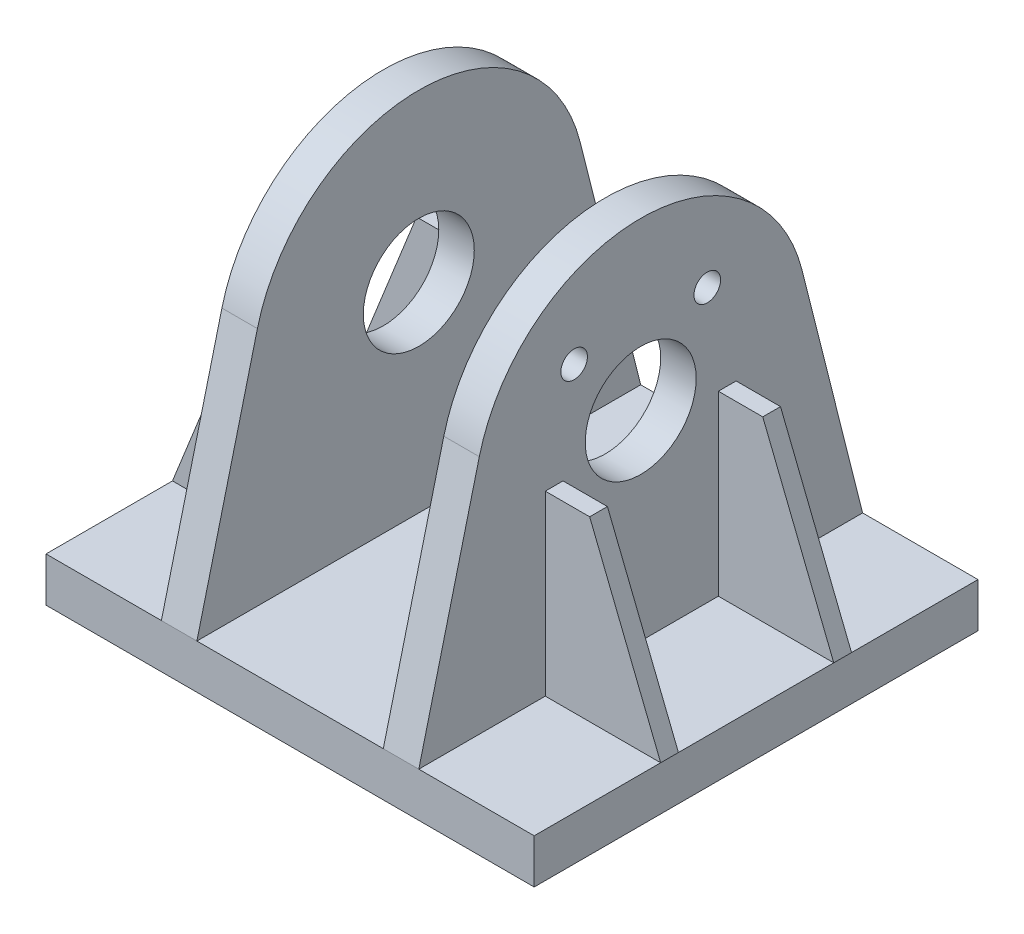
SolidWorks part; units mm, degrees
ref_plane "前视基准面" through (0, 0, 0) normal (0, 0, 1) x (1, 0, 0)
ref_plane "上视基准面" through (0, 0, 0) normal (0, 1, 0) x (1, 0, 0)
ref_plane "右视基准面" through (0, 0, 0) normal (1, 0, 0) x (0, 0, -1)
sketch "草图1" plane through (0, 0, 0) normal (0, 1, 0) x (1, 0, 0)
  line L1 (-110, 100) -> (110, 100)
  line L2 (-110, 100) -> (-110, -100)
  line L3 (-110, -100) -> (110, -100)
  line L4 (110, 100) -> (110, -100)
  dimension "D1" = 100
  dimension "D2" = 100
  dimension "D3" = 110
  dimension "D4" = 110
extrude "凸台-拉伸1" add sketch "草图1" along normal blind 20
sketch "草图2" plane through (0, 20, 0) normal (0, 1, 0) x (1, 0, 0)
  line L1 (110, 100) -> (-110, 100) construction
  line L2 (-58, 100) -> (-42, 100)
  line L3 (-58, 100) -> (-58, -100)
  line L4 (-58, -100) -> (-42, -100)
  line L5 (-42, 100) -> (-42, -100)
  line L6 (-110, -100) -> (110, -100) construction
  line L8 (42, 100) -> (58, 100)
  line L9 (42, 100) -> (42, -100)
  line L10 (42, -100) -> (58, -100)
  line L11 (58, 100) -> (58, -100)
  dimension "D1" = 16
  dimension "D2" = 16
  dimension "D3" = 42
  dimension "D4" = 42
extrude "凸台-拉伸2" add sketch "草图2" along normal blind 200
sketch "草图3" plane through (58, 0, 0) normal (1, 0, 0) x (0, 0, -1)
  line L0 (0, -1000) -> (0, 49000) construction
  line L1 (-100, 20) -> (100, 20) construction
  line L2 (-72.7303, 128.3114) -> (-100, 20)
  line L3 (-100, 20) -> (-100, 220)
  line L4 (-100, 220) -> (100, 220)
  line L5 (100, 220) -> (100, 20)
  line L6 (100, 20) -> (72.7303, 128.3114)
  circle A0 centre (0, 110) radius 25
  arc A1 (72.7303, 128.3114) -> (-72.7303, 128.3114) centre (0, 110) ccw
  dimension "D1" = 50
  dimension "D3" = 75
  dimension "D2" = 90
extrude "切除-拉伸1" cut sketch "草图3" against normal through all
sketch "草图4" plane through (58, 0, 0) normal (1, 0, 0) x (0, 0, -1)
  line L0 (-100, 20) -> (100, 20) construction
  line L1 (-43, 100) -> (-35, 100)
  line L2 (-43, 100) -> (-43, 20)
  line L3 (-43, 20) -> (-35, 20)
  line L4 (-35, 100) -> (-35, 20)
  line L6 (35, 100) -> (43, 100)
  line L7 (35, 100) -> (35, 20)
  line L8 (35, 20) -> (43, 20)
  line L9 (43, 100) -> (43, 20)
  dimension "D1" = 8
  dimension "D2" = 8
  dimension "D3" = 80
  dimension "D4" = 35
  dimension "D5" = 35
extrude "凸台-拉伸3" add sketch "草图4" along normal blind 52
sketch "草图5" plane through (0, 0, 43) normal (0, 0, 1) x (1, 0, 0)
  line L0 (110, 100) -> (78, 100)
  line L1 (110, 100) -> (58, 100) construction
  line L2 (78, 100) -> (110, 20)
  line L3 (110, 20) -> (110, 100)
  dimension "D1" = 32
extrude "切除-拉伸2" cut sketch "草图5" against normal through all
mirror "镜向1" about plane through (0, 0, 0) normal (1, 0, 0) of "切除-拉伸2", "凸台-拉伸3"
sketch "草图6" plane through (58, 0, 0) normal (1, 0, 0) x (0, 0, -1)
  line L0 (0, -1000) -> (0, 49000) construction
  line L1 (-984.0876, 143) -> (49015.9124, 143) construction
  circle A0 centre (0, 110) radius 25 construction
  circle A1 centre (-30, 143) radius 6
  circle A2 centre (30, 143) radius 6
  dimension "D4" = 12
  dimension "D5" = 12
  dimension "D1" = 33
  dimension "D2" = 30
  dimension "D3" = 30
extrude "切除-拉伸3" cut sketch "草图6" against normal blind 16
